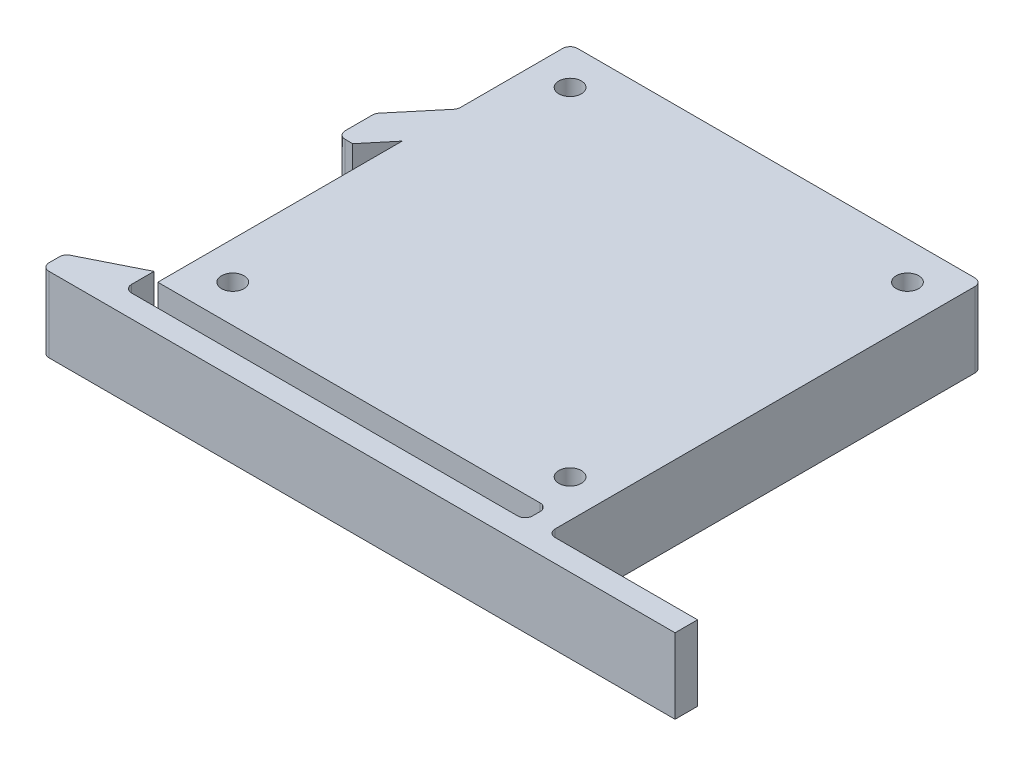
SolidWorks part; units mm, degrees
ref_plane "Front Plane" through (0, 0, 0) normal (0, 0, 1) x (1, 0, 0)
ref_plane "Top Plane" through (0, 0, 0) normal (0, 1, 0) x (1, 0, 0)
ref_plane "Right Plane" through (0, 0, 0) normal (1, 0, 0) x (0, 0, -1)
sketch "Sketch1" plane through (0, 0, 0) normal (0, 1, 0) x (1, 0, 0)
  line L1 (55, 4) -> (55, 60)
  line L2 (54, 61) -> (1, 61)
  line L3 (0, 60) -> (0, 46.362)
  line L4 (-0.2318, 45.7219) -> (-4.7682, 40.2781)
  line L5 (-5, 39.638) -> (-5, 36)
  line L7 (0, 38.6) -> (0, 6)
  line L8 (0, 6) -> (51, 6)
  line L12 (-1.5, 4) -> (-1.5, 7)
  line L15 (75, 0) -> (75, 3)
  line L16 (75, 3) -> (56, 3)
  line L17 (52, 4) -> (52, 5)
  line L18 (-4, 35) -> (-3, 35)
  line L19 (-3, 35) -> (0, 38.6)
  line L22 (-1.5, 7) -> (-8.9472, 3.2764)
  line L26 (51, 3) -> (-0.5, 3)
  line L27 (75, 0) -> (-8.5, 0)
  line L28 (-9.5, 1) -> (-9.5, 2.382)
  arc A0 (-4.7682, 40.2781) -> (-5, 39.638) centre (-4, 39.638) ccw
  arc A1 (-5, 36) -> (-4, 35) centre (-4, 36) ccw
  arc A2 (0, 46.362) -> (-0.2318, 45.7219) centre (-1, 46.362) cw
  arc A3 (1, 61) -> (0, 60) centre (1, 60) ccw
  arc A4 (55, 60) -> (54, 61) centre (54, 60) ccw
  arc A5 (56, 3) -> (55, 4) centre (56, 4) cw
  arc A6 (51, 6) -> (52, 5) centre (51, 5) cw
  arc A7 (52, 4) -> (51, 3) centre (51, 4) cw
  arc A8 (-0.5, 3) -> (-1.5, 4) centre (-0.5, 4) cw
  circle A11 centre (5, 56) radius 1.5
  circle A12 centre (50, 56) radius 1.5
  circle A13 centre (5, 11) radius 1.5
  circle A14 centre (50, 11) radius 1.5
  arc A15 (-8.9472, 3.2764) -> (-9.5, 2.382) centre (-8.5, 2.382) ccw
  arc A17 (-8.5, 0) -> (-9.5, 1) centre (-8.5, 1) cw
  point P22 (-5, 40)
  point P25 (-5, 35)
  point P28 (0, 46)
  point P31 (0, 61)
  point P34 (55, 61)
  point P37 (55, 3)
  point P40 (52, 6)
  point P43 (52, 3)
  point P48 (-9.5, 3)
  dimension "D17" = 1
  dimension "D20" = 3
  dimension "D23" = 1
  dimension "D4" = 1
  dimension "D1" = 55
  dimension "D2" = 3
  dimension "D3" = 20
  dimension "D5" = 1.5
  dimension "D6" = 3
  dimension "D7" = 55
  dimension "D8" = 8.9472
  dimension "D9" = 3
  dimension "D10" = 6
  dimension "D11" = 5
  dimension "D12" = 2
  dimension "D13" = 3.2764
  dimension "D14" = 8
  dimension "D15" = 4
  dimension "D16" = 3
  dimension "D18" = 45
  dimension "D19" = 5
  dimension "D21" = 5
  dimension "D22" = 45
  dimension "D24" = 6
  dimension "D25" = 7
  dimension "D26" = 25
extrude "Boss-Extrude1" add sketch "Sketch1" along normal blind 10
